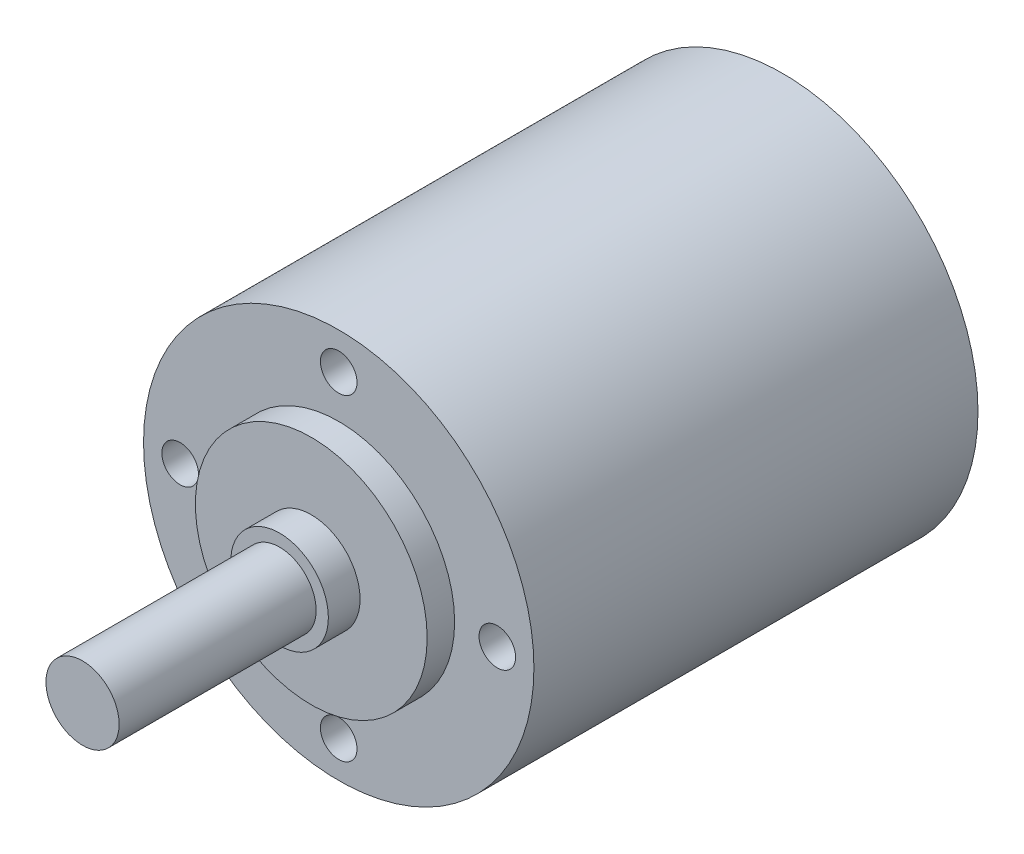
SolidWorks part; units mm, degrees
ref_plane "Plan de face" through (0, 0, 0) normal (0, 0, 1) x (1, 0, 0)
ref_plane "Plan de dessus" through (0, 0, 0) normal (0, 1, 0) x (1, 0, 0)
ref_plane "Plan de droite" through (0, 0, 0) normal (1, 0, 0) x (0, 0, -1)
sketch "Esquisse1" plane through (0, 0, 0) normal (0, 0, 1) x (1, 0, 0)
  circle A0 centre (0, 0) radius 16
extrude "Boss.-Extru.1" add sketch "Esquisse1" along normal blind 36.4
sketch "Esquisse2" plane through (0, 0, 36.4) normal (0, 0, 1) x (1, 0, 0)
  circle A0 centre (0, 0) radius 9.5
extrude "Boss.-Extru.2" add sketch "Esquisse2" along normal blind 2.25
sketch "Esquisse3" plane through (0, 0, 38.65) normal (0, 0, 1) x (1, 0, 0)
  circle A0 centre (0, 0) radius 4
extrude "Boss.-Extru.3" add sketch "Esquisse3" along normal blind 2.6
sketch "Esquisse4" plane through (0, 0, 41.25) normal (0, 0, 1) x (1, 0, 0)
  circle A0 centre (0, 0) radius 3
extrude "Boss.-Extru.4" add sketch "Esquisse4" along normal blind 16.15
sketch "Esquisse5" plane through (0, 0, 36.4) normal (0, 0, 1) x (1, 0, 0)
  line L0 (0, 0) -> (0, 16) construction
  circle A0 centre (0, 0) radius 16 construction
  circle A1 centre (0, 13) radius 1.5
  circle A2 centre (13, 0) radius 1.5
  circle A3 centre (0, -13) radius 1.5
  circle A4 centre (-13, 0) radius 1.5
  dimension "D1" = 13
  dimension "D2" = 4
extrude "Enlèv. mat.-Extru.1" cut sketch "Esquisse5" against normal blind 3.8
